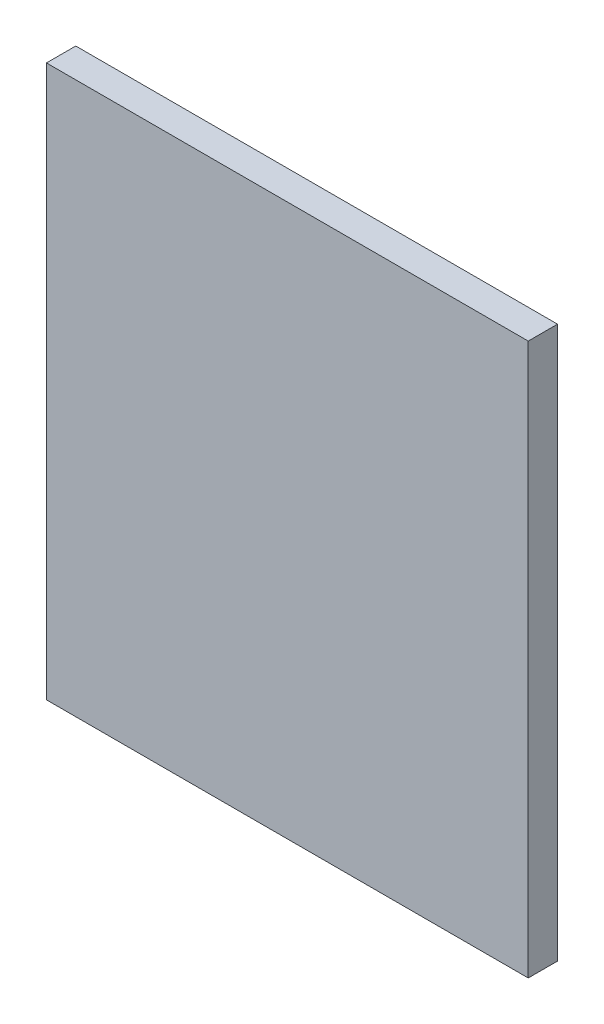
SolidWorks part; units mm, degrees
ref_plane "Front Plane" through (0, 0, 0) normal (0, 0, 1) x (1, 0, 0)
ref_plane "Top Plane" through (0, 0, 0) normal (0, 1, 0) x (1, 0, 0)
ref_plane "Right Plane" through (0, 0, 0) normal (1, 0, 0) x (0, 0, -1)
sketch "Sketch1" plane through (0, 0, 0) normal (0, 0, 1) x (1, 0, 0)
  line L1 (-43.4932, 38.6077) -> (-27.0492, 38.6077)
  line L2 (-43.4932, 38.6077) -> (-43.4932, 19.7805)
  line L3 (-43.4932, 19.7805) -> (-27.0492, 19.7805)
  line L4 (-27.0492, 38.6077) -> (-27.0492, 19.7805)
extrude "Boss-Extrude1" add sketch "Sketch1" along normal blind 1
